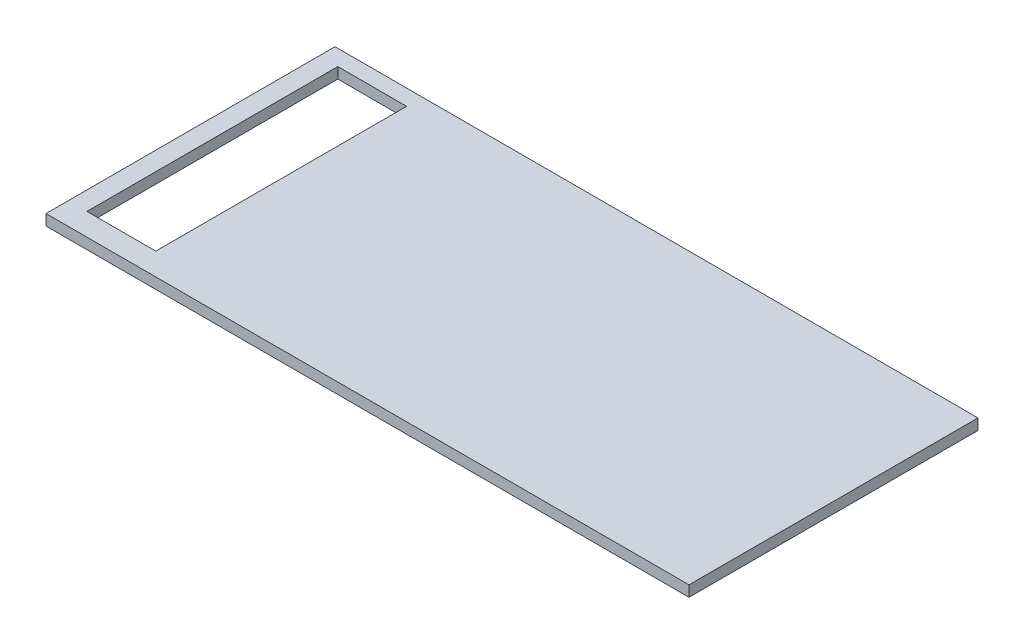
SolidWorks part; units mm, degrees
ref_plane "Front Plane" through (0, 0, 0) normal (0, 0, 1) x (1, 0, 0)
ref_plane "Top Plane" through (0, 0, 0) normal (0, 1, 0) x (1, 0, 0)
ref_plane "Right Plane" through (0, 0, 0) normal (1, 0, 0) x (0, 0, -1)
sketch "Sketch1" plane through (0, 0, 0) normal (0, 1, 0) x (1, 0, 0)
  line L1 (0, 0) -> (89, 0)
  line L2 (0, 0) -> (0, 40)
  line L3 (0, 40) -> (89, 40)
  line L4 (89, 0) -> (89, 40)
  dimension "D1" = 40
  dimension "D2" = 89
extrude "Boss-Extrude1" add sketch "Sketch1" along normal blind 1.5
sketch "Sketch2" plane through (0, 1.5, 0) normal (0, 1, 0) x (1, 0, 0)
  line L1 (2.5766, 37.8101) -> (12.0989, 37.8101)
  line L2 (2.5766, 37.8101) -> (2.5766, 3.0935)
  line L3 (2.5766, 3.0935) -> (12.0989, 3.0935)
  line L4 (12.0989, 37.8101) -> (12.0989, 3.0935)
extrude "Cut-Extrude1" cut sketch "Sketch2" against normal up to surface (1.5 mm away) up to face at (44.5, 0, -20)
